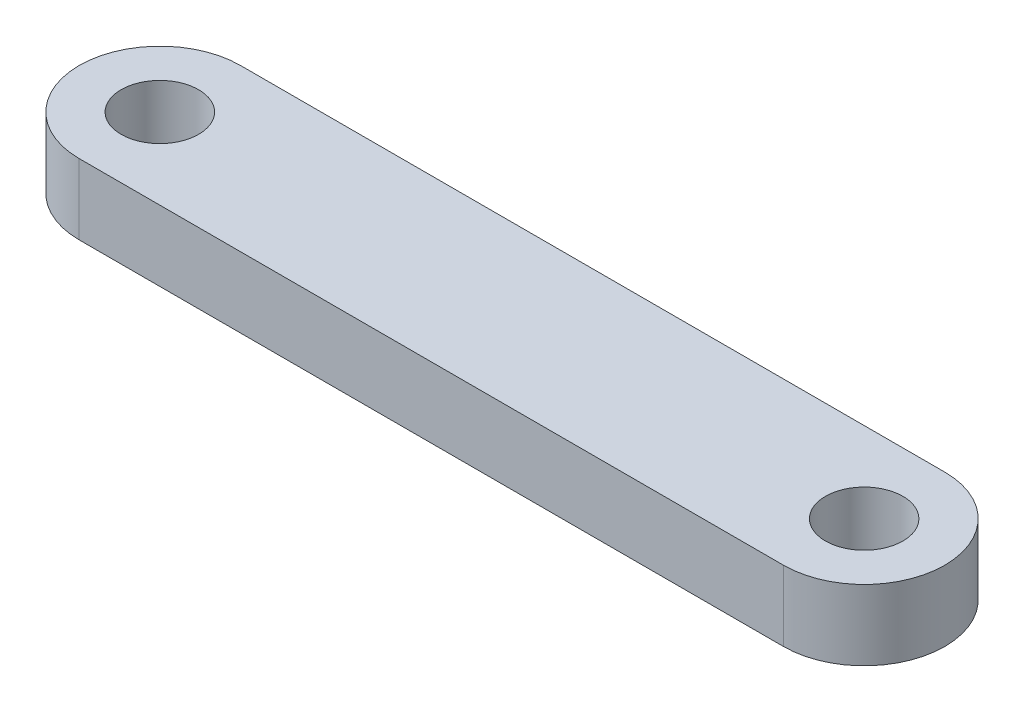
SolidWorks part; units mm, degrees
ref_plane "前视基准面" through (0, 0, 0) normal (0, 0, 1) x (1, 0, 0)
ref_plane "上视基准面" through (0, 0, 0) normal (0, 1, 0) x (1, 0, 0)
ref_plane "右视基准面" through (0, 0, 0) normal (1, 0, 0) x (0, 0, -1)
other "Configuration Table"
sketch "草图1" plane through (0, 0, 0) normal (0, 1, 0) x (1, 0, 0)
  line L1 (0, 0) -> (30, 0)
  line L3 (0, 6.87) -> (30, 6.87)
  arc A1 (0, 6.87) -> (0, 0) centre (0, 3.435) ccw
  arc A2 (30, 0) -> (30, 6.87) centre (30, 3.435) ccw
  circle A3 centre (0, 3.435) radius 1.65
  circle A4 centre (30, 3.435) radius 1.65
  dimension "D1" = 6.87
  dimension "D3" = 3.3
  dimension "D4" = 3.3
  dimension "D2" = 30
extrude "凸台-拉伸1" add sketch "草图1" along normal blind 3
